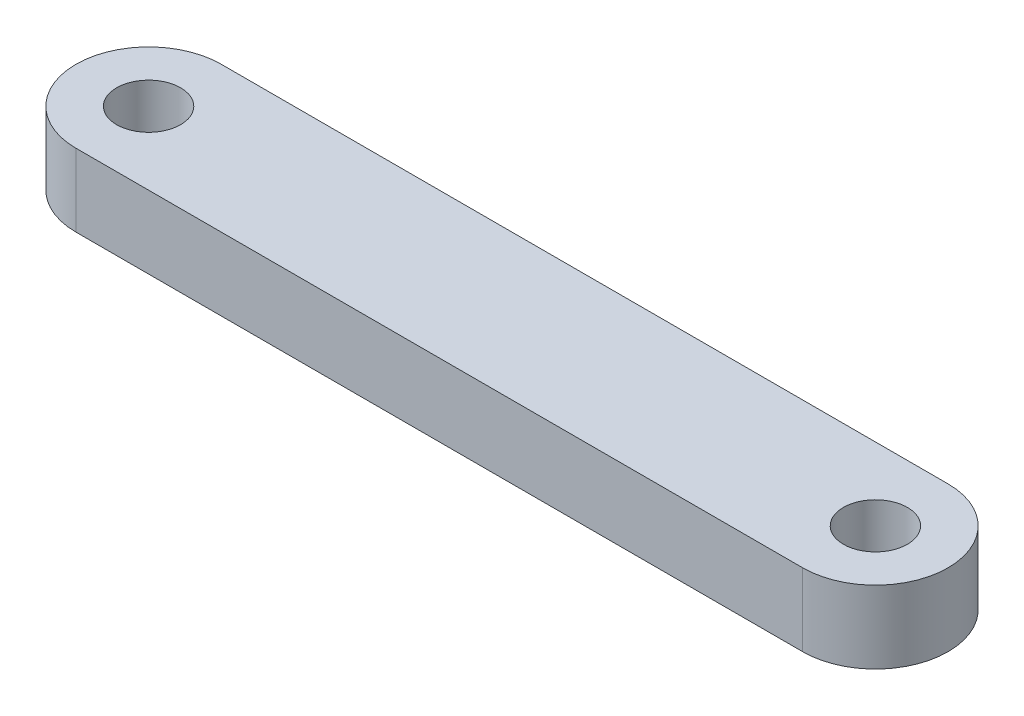
SolidWorks part; units mm, degrees
ref_plane "前视基准面" through (0, 0, 0) normal (0, 0, 1) x (1, 0, 0)
ref_plane "上视基准面" through (0, 0, 0) normal (0, 1, 0) x (1, 0, 0)
ref_plane "右视基准面" through (0, 0, 0) normal (1, 0, 0) x (0, 0, -1)
sketch "草图1" plane through (0, 0, 0) normal (0, 1, 0) x (1, 0, 0)
  line L0 (0, 0) -> (50, 0) construction
  line L1 (0, 5) -> (50, 5)
  line L2 (0, -5) -> (50, -5)
  arc A0 (0, 5) -> (0, -5) centre (0, 0) ccw
  arc A1 (50, -5) -> (50, 5) centre (50, 0) ccw
  circle A2 centre (0, 0) radius 2.2
  circle A3 centre (50, 0) radius 2.2
  point P3 (25, 0)
  dimension "D3" = 4.4
  dimension "D1" = 10
  dimension "D2" = 50
extrude "凸台-拉伸2" add sketch "草图1" along normal blind 5
